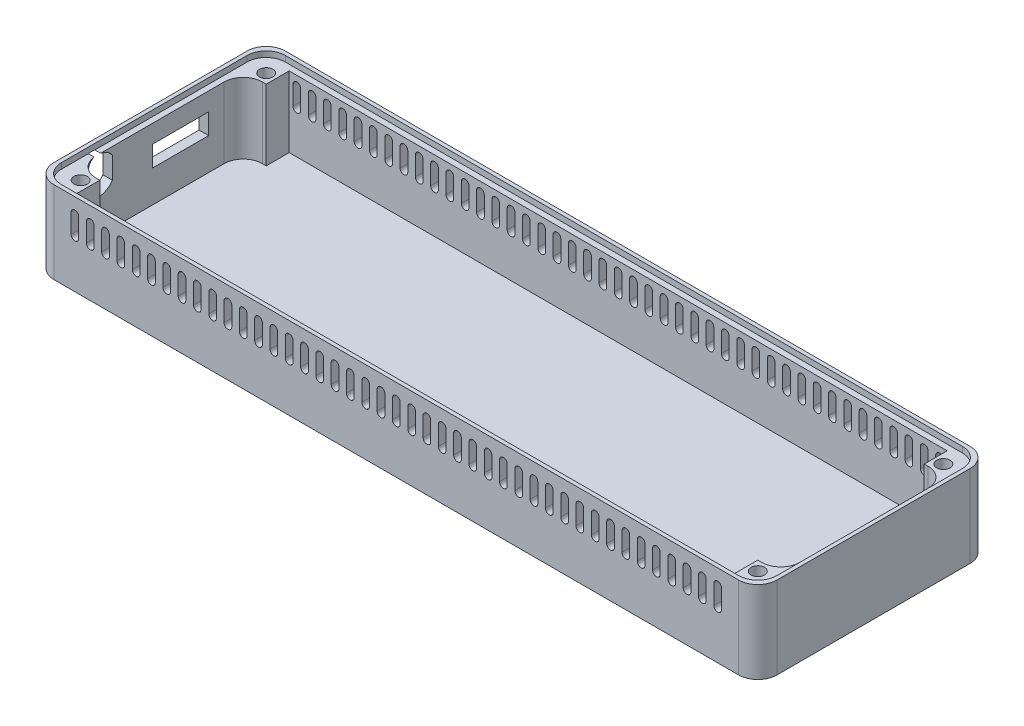
SolidWorks part; units mm, degrees
ref_plane "Front Plane" through (0, 0, 0) normal (0, 0, 1) x (1, 0, 0)
ref_plane "Top Plane" through (0, 0, 0) normal (0, 1, 0) x (1, 0, 0)
ref_plane "Right Plane" through (0, 0, 0) normal (1, 0, 0) x (0, 0, -1)
sketch "Sketch1" plane through (0, 0, 0) normal (0, 1, 0) x (1, 0, 0)
  line L0 (-98.5, 30.25) -> (90.5, 30.25)
  line L1 (82.5, -27.75) -> (-82.5, -27.75)
  line L2 (82.5, -27.75) -> (82.5, 27.75)
  line L3 (82.5, 27.75) -> (-82.5, 27.75)
  line L4 (-82.5, -27.75) -> (-82.5, 27.75)
  line L5 (82.5, -27.75) -> (-82.5, 27.75) construction
  line L6 (82.5, 27.75) -> (-82.5, -27.75) construction
  line L7 (90.5, 30.25) -> (90.5, -30.25)
  line L8 (90.5, -30.25) -> (-98.5, -30.25)
  line L9 (-98.5, -30.25) -> (-98.5, 30.25)
  line L10 (82.5, 30.25) -> (82.5, 27.75) construction
  point P0 (0, 0)
  point P10 (90.5, 0)
  dimension "D1" = 55.5
  dimension "D2" = 165
  dimension "D3" = 2.5
  dimension "D4" = 8
  dimension "D5" = 16
extrude "Boss-Extrude1" add sketch "Sketch1" along normal blind 1.5 contours L4 L1 L2 L3 | L9 L8 L7 L0 L1 L4 L3 L2
sketch "Sketch2" plane through (0, 1.5, 0) normal (0, 1, 0) x (1, 0, 0)
  line L4 (-98.5, 30.25) -> (-98.5, -30.25)
  line L5 (-98.5, -30.25) -> (90.5, -30.25)
  line L6 (90.5, -30.25) -> (90.5, 30.25)
  line L7 (90.5, 30.25) -> (-98.5, 30.25)
  line L8 (-98.5, 30.25) -> (-98.5, -30.25)
  line L9 (-98.5, -30.25) -> (90.5, -30.25)
  line L10 (90.5, -30.25) -> (90.5, 30.25)
  line L11 (90.5, 30.25) -> (-98.5, 30.25)
  dimension "D1" = 0
extrude "Extrude-Thin1" add sketch "Sketch2" along normal blind 20 thin thin type one direction reverse wall 2.5
sketch "Sketch3" plane through (-98.5, 0, 0) normal (-1, 0, 0) x (0, 0, 1)
  line L0 (20.3504, 18.053) -> (20.3504, 12.333)
  line L1 (12.4398, 18.053) -> (12.4398, 12.333)
  arc A0 (20.3504, 18.053) -> (12.4398, 18.053) centre (16.3951, 15.193) ccw
  arc A1 (12.4398, 12.333) -> (20.3504, 12.333) centre (16.3951, 15.193) ccw
  point P6 (0, 0)
extrude "Cut-Extrude1" cut sketch "Sketch3" against normal up to next
sketch "Sketch4" plane through (-98.5, 0, 0) normal (-1, 0, 0) x (0, 0, 1)
  line L1 (-12.7031, 15.2555) -> (1.9399, 15.2555)
  line L2 (-12.7031, 15.2555) -> (-12.7031, 9.8739)
  line L3 (-12.7031, 9.8739) -> (1.9399, 9.8739)
  line L4 (1.9399, 15.2555) -> (1.9399, 9.8739)
extrude "Cut-Extrude2" cut sketch "Sketch4" against normal up to next
sketch "Sketch5" plane through (0, 1.5, 0) normal (0, 1, 0) x (1, 0, 0)
  line L1 (-96, 27.75) -> (-90, 27.75)
  line L2 (-96, 27.75) -> (-96, 21.75)
  line L3 (-96, 21.75) -> (-90, 21.75)
  line L4 (-90, 27.75) -> (-90, 21.75)
  line L5 (88, 27.75) -> (82, 27.75)
  line L6 (88, 27.75) -> (88, 21.75)
  line L7 (88, 21.75) -> (82, 21.75)
  line L8 (82, 27.75) -> (82, 21.75)
  line L9 (88, -27.75) -> (82, -27.75)
  line L10 (88, -27.75) -> (88, -21.75)
  line L11 (88, -21.75) -> (82, -21.75)
  line L12 (82, -27.75) -> (82, -21.75)
  line L13 (-96, -27.75) -> (-90, -27.75)
  line L14 (-96, -27.75) -> (-96, -21.75)
  line L15 (-96, -21.75) -> (-90, -21.75)
  line L16 (-90, -27.75) -> (-90, -21.75)
  point P20 (0, 0)
  point P21 (0, 0)
  point P22 (0, 0)
  point P23 (0, 0)
  point P24 (-82.3963, -16.5897)
  dimension "D1" = 6
  dimension "D2" = 6
extrude "Boss-Extrude2" add sketch "Sketch5" along normal through all
sketch "Sketch6" plane through (0, 21.5, 0) normal (0, 1, 0) x (1, 0, 0)
  line L0 (89.5, 29.25) -> (-97.5, 29.25)
  line L1 (-97.5, 29.25) -> (-97.5, -29.25)
  line L2 (-97.5, -29.25) -> (89.5, -29.25)
  line L3 (89.5, -29.25) -> (89.5, 29.25)
  line L4 (90.5, 30.25) -> (-98.5, 30.25)
  line L5 (-98.5, 30.25) -> (-98.5, -30.25)
  line L6 (-98.5, -30.25) -> (90.5, -30.25)
  line L7 (90.5, -30.25) -> (90.5, 30.25)
  line L8 (90.5, 30.25) -> (-98.5, 30.25) construction
  line L9 (-98.5, 30.25) -> (-98.5, -30.25) construction
  line L10 (-98.5, -30.25) -> (90.5, -30.25) construction
  line L11 (90.5, -30.25) -> (90.5, 30.25) construction
  dimension "D1" = 0
  dimension "D2" = 1
extrude "Cut-Extrude3" cut sketch "Sketch6" against normal blind 1.5
fillet "Fillet1" radius 5 4 edges at (88, 10.75, -21.75) (88, 10.75, 21.75) (-96, 10.75, 21.75) (-96, 10.75, -21.75)
fillet "Fillet2" radius 5 4 edges at (89.5, 20.75, -29.25) (-97.5, 20.75, 29.25) (89.5, 20.75, 29.25) (-97.5, 20.75, -29.25)
fillet "Fillet3" radius 5 4 edges at (90.5, 10.75, -30.25) (-98.5, 10.75, 30.25) (-98.5, 10.75, -30.25) (90.5, 10.75, 30.25)
hole_wizard "Hole1" positions "Sketch7" profile "Sketch8" legacy
sketch "Sketch7" plane through (0, 20, 0) normal (0, 1, 0) x (1, 0, 0)
  point P0 (-92.5, 24.25)
  point P2 (-92.5, -24.25)
  point P4 (84.5, -24.25)
  point P7 (84.5, 24.25)
  point P10 (0, 0)
  point P11 (0, 0)
  point P12 (0, 0)
  point P13 (84.5, -24.25)
  point P15 (84.5, 24.25)
  point P17 (-92.5, 24.25)
sketch "Sketch8" plane through (-92.5, 20, -24.25) normal (1, 0, 0) x (0, 0, 1)
  line L0 (0, 0) -> (0, 6)
  line L1 (0, 6) -> (1.25, 6)
  line L2 (1.25, 6) -> (1.25, 2.95)
  line L3 (1.25, 2.95) -> (1.75, 2.95)
  line L4 (1.75, 2.95) -> (1.75, 0)
  line L5 (1.75, 0) -> (0, 0)
  line L6 (0, 110) -> (0, -10) construction
  dimension "Diameter" = 2.5
  dimension "Depth" = 6
  dimension "C-Bore Diameter" = 3.5
  dimension "C-Bore Depth" = 2.95
sketch "Sketch9" plane through (0, 0, 30.25) normal (0, 0, 1) x (1, 0, 0)
  line L0 (0, 12.5) -> (0, 17.5) construction
  line L1 (-1, 12.5) -> (-1, 17.5)
  line L2 (1, 12.5) -> (1, 17.5)
  line L3 (-93.5, 21.5) -> (85.5, 21.5) construction
  arc A0 (-1, 12.5) -> (1, 12.5) centre (0, 12.5) ccw
  arc A1 (1, 17.5) -> (-1, 17.5) centre (0, 17.5) ccw
  point P3 (0, 15)
  dimension "D1" = 2
  dimension "D2" = 5
  dimension "D3" = 4
extrude "Cut-Extrude4" cut sketch "Sketch9" against normal through all
pattern_linear "LPattern1" count 23 spacing 4 along (-1, 0, 0) of "Cut-Extrude4"
pattern_linear "LPattern2" count 21 spacing 4 along (1, 0, 0) of "Cut-Extrude4"
